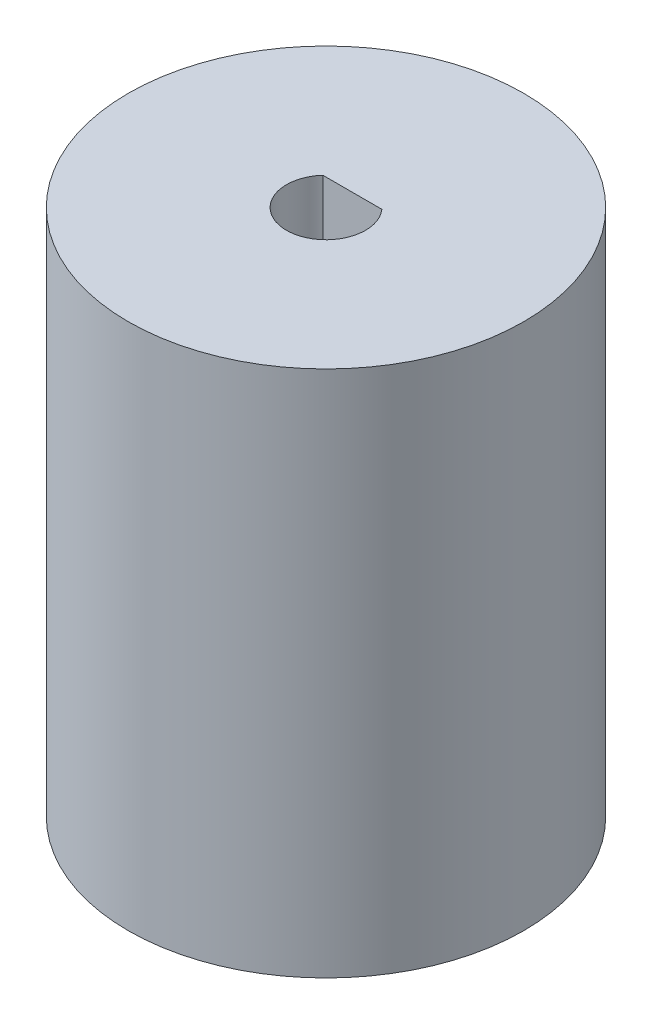
SolidWorks part; units mm, degrees
ref_plane "Front Plane" through (0, 0, 0) normal (0, 0, 1) x (1, 0, 0)
ref_plane "Top Plane" through (0, 0, 0) normal (0, 1, 0) x (1, 0, 0)
ref_plane "Right Plane" through (0, 0, 0) normal (1, 0, 0) x (0, 0, -1)
sketch "Sketch1" plane through (0, 0, 0) normal (0, 1, 0) x (1, 0, 0)
  line L0 (0, -1.2479) -> (0, -0.2479) construction
  line L1 (-1.118, -0.2479) -> (1.118, -0.2479)
  circle A0 centre (0, -1.2479) radius 7.5
  circle A1 centre (0, -1.2479) radius 1.5
  dimension "D2" = 15
  dimension "D3" = 1
  dimension "D1" = 3
extrude "Boss-Extrude1" add sketch "Sketch1" along normal blind 20 contours L1 A1 | A0 A1
